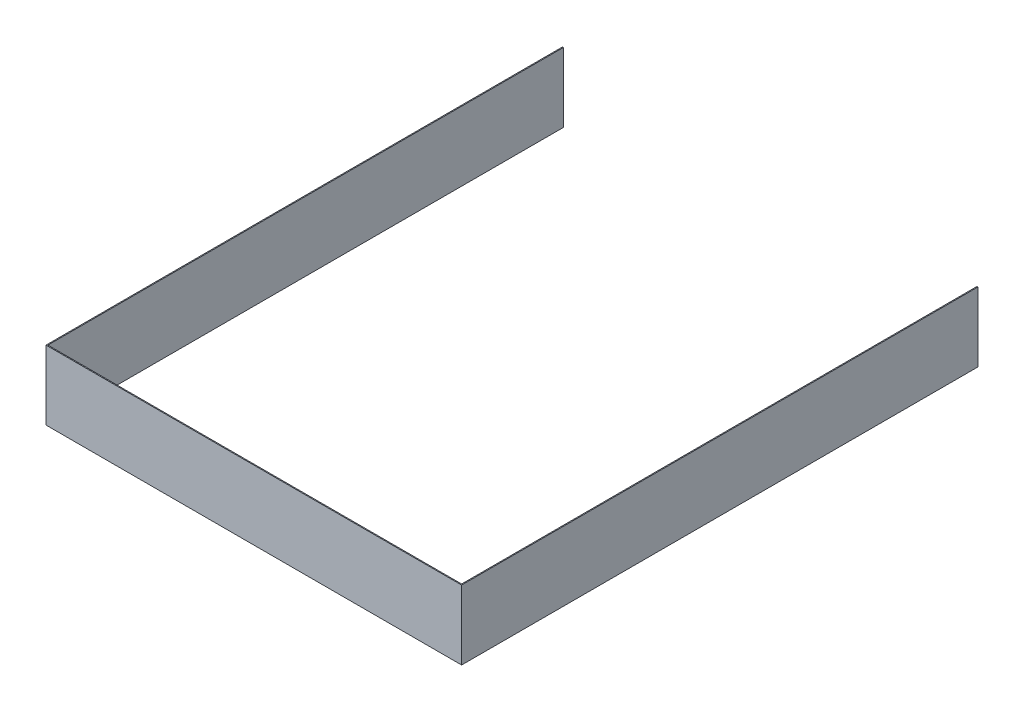
SolidWorks part; units mm, degrees
ref_plane "Front Plane" through (0, 0, 0) normal (0, 0, 1) x (1, 0, 0)
ref_plane "Top Plane" through (0, 0, 0) normal (0, 1, 0) x (1, 0, 0)
ref_plane "Right Plane" through (0, 0, 0) normal (1, 0, 0) x (0, 0, -1)
other "Configuration Table"
sketch "Sketch1" plane through (0, 0, 0) normal (0, 1, 0) x (1, 0, 0)
  line L0 (20, 800) -> (20, -20)
  line L1 (20, -20) -> (680, -20)
  line L2 (680, -20) -> (680, 800)
  line L3 (680, 800) -> (678.5, 800)
  line L4 (678.5, 800) -> (678.5, -18.5)
  line L5 (678.5, -18.5) -> (21.5, -18.5)
  line L6 (21.5, -18.5) -> (21.5, 800)
  line L7 (21.5, 800) -> (20, 800)
extrude "PACK_plint_U_1" add sketch "Sketch1" along normal blind 110 from offset 10 separate body
